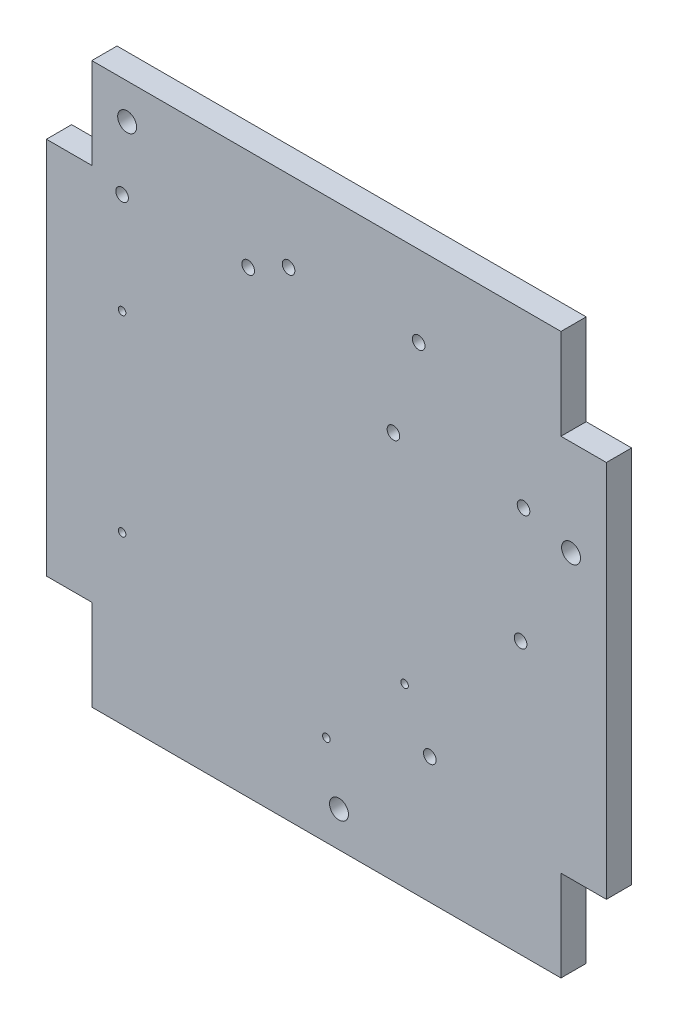
SolidWorks part; units mm, degrees
ref_plane "Płaszczyzna przednia" through (0, 0, 0) normal (0, 0, 1) x (1, 0, 0)
ref_plane "Płaszczyzna górna" through (0, 0, 0) normal (0, 1, 0) x (1, 0, 0)
ref_plane "Płaszczyzna prawa" through (0, 0, 0) normal (1, 0, 0) x (0, 0, -1)
sketch "Szkic2" plane through (0, 0, 0) normal (0, 0, 1) x (1, 0, 0)
  line L1 (0, 0) -> (111, 0)
  line L2 (0, 0) -> (0, 111)
  line L3 (0, 111) -> (111, 111)
  line L4 (111, 0) -> (111, 111)
  line L5 (0, 93) -> (9, 93)
  line L6 (0, 93) -> (0, 111)
  line L7 (0, 111) -> (9, 111)
  line L8 (9, 93) -> (9, 111)
  line L9 (102, 93) -> (111, 93)
  line L10 (102, 93) -> (102, 111)
  line L11 (102, 111) -> (111, 111)
  line L12 (111, 93) -> (111, 111)
  line L13 (102, 18) -> (111, 18)
  line L14 (102, 18) -> (102, 0)
  line L15 (102, 0) -> (111, 0)
  line L16 (111, 18) -> (111, 0)
  line L17 (0, 18) -> (9, 18)
  line L18 (0, 18) -> (0, 0)
  line L19 (0, 0) -> (9, 0)
  line L20 (9, 18) -> (9, 0)
  circle A0 centre (15, 91) radius 1.25
  circle A1 centre (40, 91) radius 1.25
  circle A2 centre (48, 95) radius 1.25
  circle A3 centre (68.7906, 77) radius 1.25
  circle A4 centre (73.7906, 95) radius 1.25
  circle A5 centre (94.5812, 77) radius 1.25
  circle A6 centre (15, 71) radius 0.75
  circle A7 centre (71, 35) radius 0.75
  circle A8 centre (15, 33) radius 0.75
  circle A9 centre (55.5, 18) radius 0.75
  circle A10 centre (76, 25) radius 1.25
  circle A11 centre (94, 53.8444) radius 1.25
  circle A12 centre (16, 104) radius 1.875
  circle A13 centre (58, 7) radius 1.875
  circle A14 centre (104, 74) radius 1.875
  dimension "D11" = 2.5
  dimension "D12" = 20
  dimension "D13" = 15
  dimension "D14" = 2.5
  dimension "D15" = 20
  dimension "D16" = 25
  dimension "D17" = 2.5
  dimension "D18" = 16
  dimension "D19" = 8
  dimension "D20" = 2.5
  dimension "D21" = 18
  dimension "D22" = 27.5
  dimension "D23" = 2.5
  dimension "D24" = 5
  dimension "D25" = 18
  dimension "D26" = 2.5
  dimension "D27" = 27.5
  dimension "D28" = 18
  dimension "D29" = 1.5
  dimension "D30" = 1.5
  dimension "D31" = 15
  dimension "D32" = 56
  dimension "D33" = 36
  dimension "D34" = 20
  dimension "D35" = 1.5
  dimension "D36" = 1.5
  dimension "D37" = 33
  dimension "D38" = 40.5
  dimension "D39" = 15
  dimension "D40" = 15
  dimension "D41" = 2.5
  dimension "D42" = 25
  dimension "D43" = 35
  dimension "D44" = 2.5
  dimension "D45" = 18
  dimension "D46" = 34
  dimension "D47" = 3.75
  dimension "D48" = 7
  dimension "D49" = 7
  dimension "D50" = 3.75
  dimension "D51" = 58
  dimension "D52" = 7
  dimension "D53" = 3.75
  dimension "D54" = 7
  dimension "D1" = 111
  dimension "D2" = 111
  dimension "D3" = 18
  dimension "D4" = 9
  dimension "D5" = 18
  dimension "D6" = 9
  dimension "D7" = 18
  dimension "D8" = 9
  dimension "D9" = 18
  dimension "D10" = 9
  dimension "D55" = 37
extrude "Dodanie-wyciągnięcie1" add sketch "Szkic2" along normal blind 5 contours L17 L20 L1 L14 L13 L4 L9 L10 L3 L8 L5 L2 A11 A10 A9 A8 A7 A6 A5 A4 A3 A2 A1 A0
sketch "Szkic4" plane through (0, 0, 5) normal (0, 0, 1) x (1, 0, 0)
